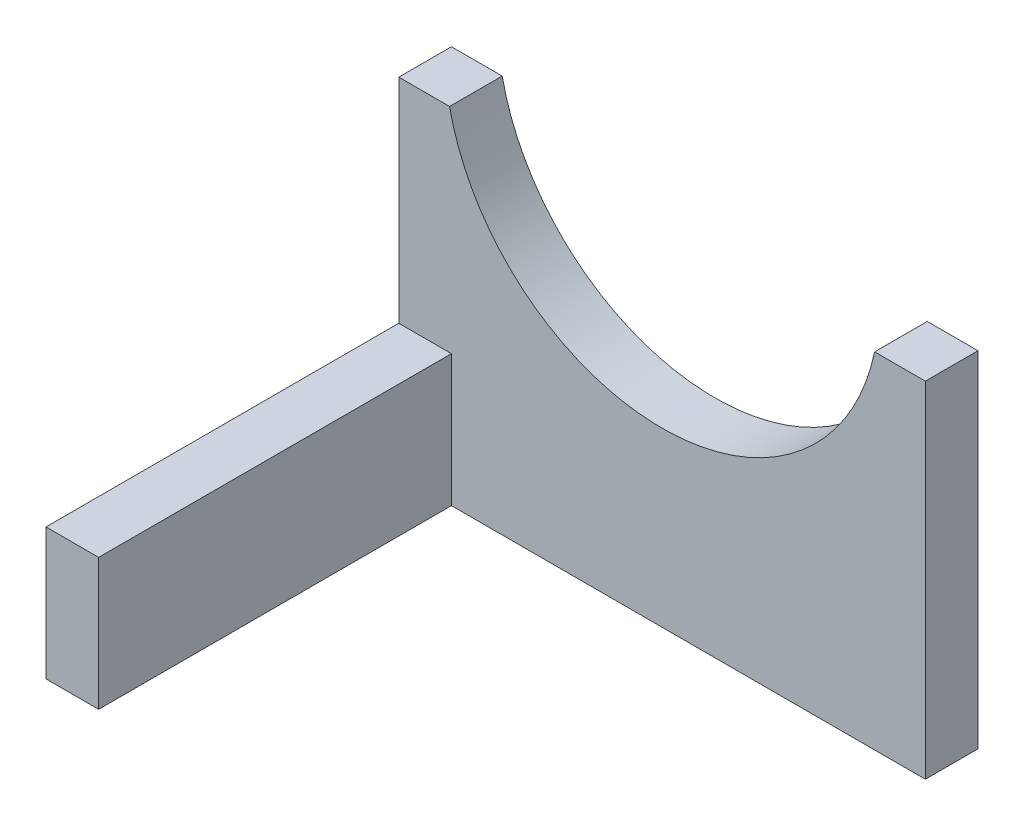
SolidWorks part; units mm, degrees
ref_plane "Front Plane" through (0, 0, 0) normal (0, 0, 1) x (1, 0, 0)
ref_plane "Top Plane" through (0, 0, 0) normal (0, 1, 0) x (1, 0, 0)
ref_plane "Right Plane" through (0, 0, 0) normal (1, 0, 0) x (0, 0, -1)
sketch "Sketch1" plane through (0, 0, 0) normal (0, 0, 1) x (1, 0, 0)
  line L0 (0, 16.632) -> (50.8, 16.632) construction
  line L1 (0, 0) -> (50.8, 0)
  line L2 (0, 0) -> (0, 33.264)
  line L3 (0, 33.264) -> (50.8, 33.264) construction
  line L4 (50.8, 0) -> (50.8, 33.264)
  line L5 (25.4, 16.632) -> (25.4, 33.264) construction
  line L6 (25.4, 33.264) -> (25.4, 37.587)
  line L7 (4.8958, 33.264) -> (0, 33.264)
  line L8 (45.9042, 33.264) -> (50.8, 33.264)
  circle A0 centre (25.4, 37.587) radius 20.955 construction
  arc A1 (4.8958, 33.264) -> (45.9042, 33.264) centre (25.4, 37.587) ccw
  dimension "D1" = 41.91
  dimension "D2" = 50.8
extrude "Boss-Extrude1" add sketch "Sketch1" along normal blind 5.08 contours A1 L7 L2 L1 L4 L8
sketch "Sketch2" plane through (0, 0, 0) normal (1, 0, 0) x (0, 0, -1)
  line L0 (-5.08, 0) -> (-39.116, 0) construction
  line L2 (-5.08, 0) -> (-39.116, 0)
  line L3 (-5.08, 0) -> (-5.08, 12.7)
  line L4 (-5.08, 12.7) -> (-39.116, 12.7)
  line L5 (-39.116, 0) -> (-39.116, 12.7)
  point P6 (0, 0)
  dimension "D1" = 34.036
  dimension "D2" = 12.7
extrude "Boss-Extrude2" add sketch "Sketch2" along normal blind 5.08
